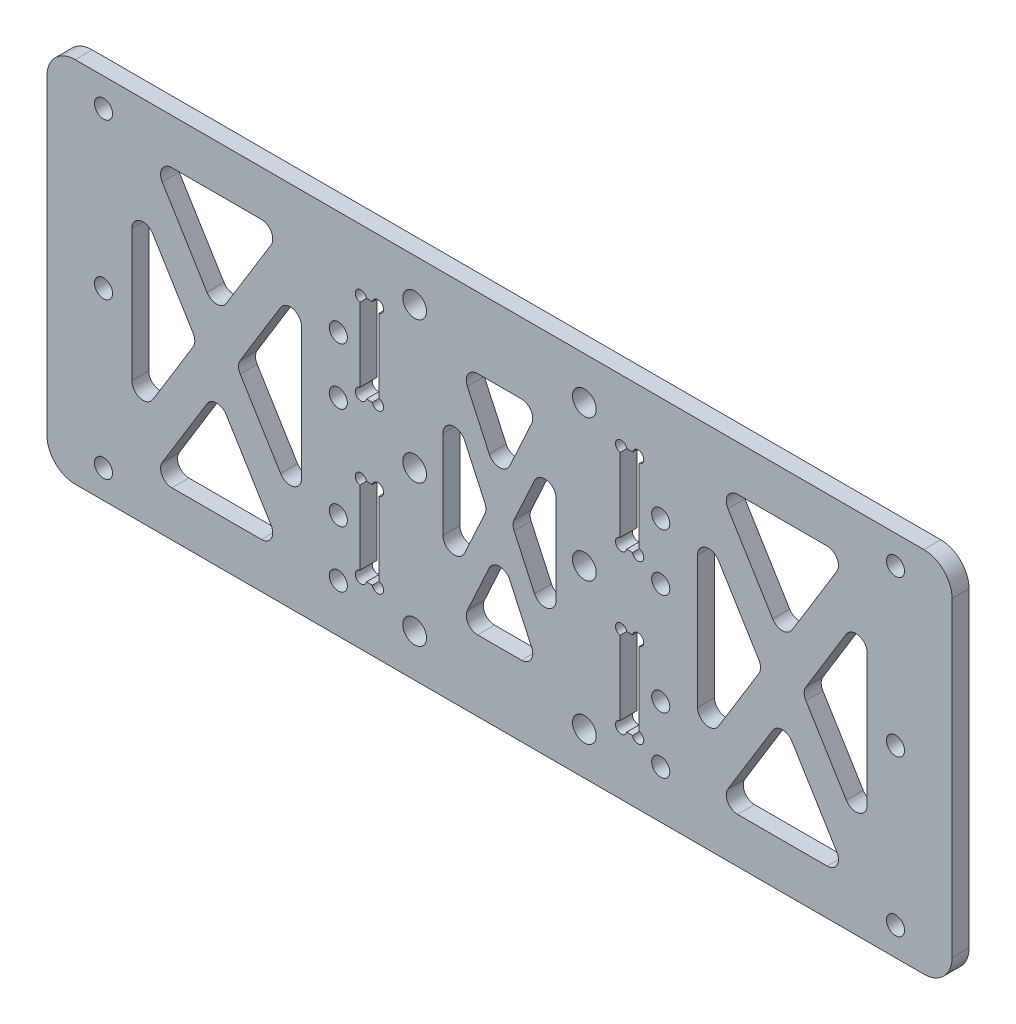
SolidWorks part; units mm, degrees
ref_plane "前视基准面" through (0, 0, 0) normal (0, 0, 1) x (1, 0, 0)
ref_plane "上视基准面" through (0, 0, 0) normal (0, 1, 0) x (1, 0, 0)
ref_plane "右视基准面" through (0, 0, 0) normal (1, 0, 0) x (0, 0, -1)
other "Configuration Table"
sketch "草图1" plane through (0, 0, 0) normal (0, 0, 1) x (1, 0, 0)
  line L1 (0, 0) -> (160, 0)
  line L2 (0, 0) -> (0, 65)
  line L3 (0, 65) -> (160, 65)
  line L4 (160, 0) -> (160, 65)
  dimension "D1" = 160
  dimension "D2" = 65
extrude "凸台-拉伸1" add sketch "草图1" along normal blind 3
sketch "草图2" plane through (0, 0, 3) normal (0, 0, 1) x (1, 0, 0)
  line L0 (80, 65) -> (80, 0) construction
  line L1 (160, 65) -> (0, 65) construction
  line L2 (0, 0) -> (160, 0) construction
  line L3 (150, 0) -> (150, 60) construction
  line L4 (160, 0) -> (160, 65) construction
  circle A0 centre (150, 60) radius 1.6
  circle A1 centre (150, 32.5) radius 1.6
  circle A2 centre (150, 5) radius 1.6
  circle A3 centre (10, 5) radius 1.6
  circle A4 centre (10, 32.5) radius 1.6
  circle A5 centre (10, 60) radius 1.6
  dimension "D2" = 60
  dimension "D3" = 27.5
  dimension "D4" = 27.5
  dimension "D5" = 3.2
  dimension "D1" = 10
extrude "切除-拉伸1" cut sketch "草图2" against normal through all
sketch "草图3" plane through (0, 0, 3) normal (0, 0, 1) x (1, 0, 0)
  line L0 (80, 65) -> (80, 0) construction
  line L1 (160, 65) -> (0, 65) construction
  line L2 (0, 0) -> (160, 0) construction
  line L3 (65, 32.5) -> (80, 32.5) construction
  circle A0 centre (65, 57.5) radius 2.1
  circle A1 centre (65, 32.5) radius 2.1
  circle A3 centre (65, 7.5) radius 2.1
  circle A4 centre (95, 7.5) radius 2.1
  circle A5 centre (95, 32.5) radius 2.1
  circle A6 centre (95, 57.5) radius 2.1
  dimension "D1" = 4.2
  dimension "D2" = 30
  dimension "D3" = 25
extrude "切除-拉伸2" cut sketch "草图3" against normal through all
sketch "草图4" plane through (0, 0, 3) normal (0, 0, 1) x (1, 0, 0)
  line L0 (80, 65) -> (80, 0) construction
  line L1 (160, 65) -> (0, 65) construction
  line L2 (0, 0) -> (160, 0) construction
  line L3 (80, 32.5) -> (70.6836, 32.5) construction
  line L4 (55.5, 54) -> (58.5, 54)
  line L5 (55.5, 54) -> (55.5, 39)
  line L6 (55.5, 39) -> (58.5, 39)
  line L7 (58.5, 54) -> (58.5, 39)
  line L8 (55.5, 26) -> (58.5, 26)
  line L9 (55.5, 11) -> (55.5, 26)
  line L10 (55.5, 11) -> (58.5, 11)
  line L11 (58.5, 11) -> (58.5, 26)
  line L12 (101.5, 11) -> (101.5, 26)
  line L13 (104.5, 11) -> (101.5, 11)
  line L14 (104.5, 11) -> (104.5, 26)
  line L15 (104.5, 26) -> (101.5, 26)
  line L16 (101.5, 54) -> (101.5, 39)
  line L17 (104.5, 39) -> (101.5, 39)
  line L18 (104.5, 54) -> (104.5, 39)
  line L19 (104.5, 54) -> (101.5, 54)
  dimension "D1" = 43
  dimension "D2" = 3
  dimension "D3" = 15
  dimension "D4" = 13
extrude "切除-拉伸3" cut sketch "草图4" against normal through all
sketch "草图5" plane through (0, 0, 3) normal (0, 0, 1) x (1, 0, 0)
  circle A0 centre (58.5, 54) radius 1
  circle A1 centre (55.5, 54) radius 1
  circle A2 centre (58.5, 39) radius 1
  circle A3 centre (55.5, 39) radius 1
  circle A4 centre (58.5, 26) radius 1
  circle A5 centre (55.5, 26) radius 1
  circle A6 centre (58.5, 11) radius 1
  circle A7 centre (55.5, 11) radius 1
  circle A8 centre (104.5, 54) radius 1
  circle A9 centre (101.5, 54) radius 1
  circle A10 centre (104.5, 39) radius 1
  circle A11 centre (101.5, 39) radius 1
  circle A12 centre (104.5, 26) radius 1
  circle A13 centre (101.5, 26) radius 1
  circle A14 centre (104.5, 11) radius 1
  circle A15 centre (101.5, 11) radius 1
  dimension "D1" = 2
extrude "切除-拉伸4" cut sketch "草图5" against normal through all
fillet "圆角1" radius 5 4 edges at (160, 0, 1.5) (160, 65, 1.5) (0, 0, 1.5) (0, 65, 1.5)
sketch "草图6" plane through (0, 0, 3) normal (0, 0, 1) x (1, 0, 0)
  line L0 (108.5, 52.8013) -> (108.5, -0.3338) construction
  line L1 (155, 65) -> (5, 65) construction
  line L2 (80, 65) -> (80, 0) construction
  line L3 (5, 0) -> (155, 0) construction
  line L4 (104.5, 12) -> (104.5, 25) construction
  circle A0 centre (108.5, 46.5) radius 1.6
  circle A1 centre (108.5, 36.5) radius 1.6
  circle A2 centre (108.5, 18.5) radius 1.6
  circle A3 centre (108.5, 8.5) radius 1.6
  circle A4 centre (51.5, 8.5) radius 1.6
  circle A5 centre (51.5, 18.5) radius 1.6
  circle A6 centre (51.5, 36.5) radius 1.6
  circle A7 centre (51.5, 46.5) radius 1.6
  dimension "D1" = 18.5
  dimension "D2" = 10
  dimension "D3" = 18
  dimension "D4" = 10
  dimension "D5" = 3.2
  dimension "D6" = 4
extrude "切除-拉伸5" cut sketch "草图6" against normal blind 10
sketch "草图7" plane through (0, 0, 3) normal (0, 0, 1) x (1, 0, 0)
  line L0 (155, 65) -> (5, 65) construction
  line L1 (115, 57) -> (145, 57)
  line L2 (115, 57) -> (115, 8)
  line L3 (115, 8) -> (145, 8)
  line L4 (145, 57) -> (145, 8)
  line L5 (5, 0) -> (155, 0) construction
  line L6 (160, 5) -> (160, 60) construction
  line L7 (80, 65) -> (80, 0) construction
  line L8 (15, 57) -> (15, 8)
  line L9 (45, 8) -> (15, 8)
  line L10 (45, 57) -> (45, 8)
  line L11 (45, 57) -> (15, 57)
  dimension "D1" = 8
  dimension "D2" = 8
  dimension "D3" = 15
  dimension "D4" = 30
extrude "切除-拉伸6" cut sketch "草图7" against normal blind 10
sketch "草图8" plane through (0, 0, 3) normal (0, 0, 1) x (1, 0, 0)
  line L0 (80, 52.5) -> (80, 65) construction
  line L1 (70, 52.5) -> (90, 52.5)
  line L2 (70, 52.5) -> (70, 12.5)
  line L3 (70, 12.5) -> (90, 12.5)
  line L4 (90, 52.5) -> (90, 12.5)
  line L5 (155, 65) -> (5, 65) construction
  line L6 (90, 32.5) -> (160, 32.5) construction
  line L7 (160, 5) -> (160, 60) construction
  dimension "D1" = 20
  dimension "D2" = 40
extrude "切除-拉伸7" cut sketch "草图8" against normal blind 10
sketch "草图9" plane through (0, 0, 3) normal (0, 0, 1) x (1, 0, 0)
  line L0 (115, 13.7454) -> (115, 8)
  line L2 (90, 15.5496) -> (90, 12.5)
  line L4 (141.4824, 57) -> (130, 38.2454)
  line L5 (115, 51.2546) -> (126.4824, 32.5)
  line L6 (87, 52.5) -> (80, 37.2851)
  line L7 (70, 49.4504) -> (77.7985, 32.5)
  line L8 (145, 51.2546) -> (133.5176, 32.5)
  line L9 (118.5176, 57) -> (130, 38.2454)
  line L10 (90, 49.4504) -> (82.2015, 32.5)
  line L11 (73, 52.5) -> (80, 37.2851)
  line L12 (115, 57) -> (115, 51.2546)
  line L13 (115, 8) -> (118.5176, 8)
  line L14 (145, 57) -> (145, 51.2546)
  line L15 (115, 57) -> (118.5176, 57)
  line L16 (70, 52.5) -> (73, 52.5)
  line L17 (90, 52.5) -> (90, 49.4504)
  line L18 (70, 12.5) -> (73, 12.5)
  line L19 (70, 52.5) -> (70, 49.4504)
  line L20 (87, 12.5) -> (90, 12.5)
  line L21 (87, 52.5) -> (90, 52.5)
  line L22 (70, 12.5) -> (90, 12.5) construction
  line L23 (90, 52.5) -> (70, 52.5) construction
  line L24 (70, 15.5496) -> (70, 12.5)
  line L25 (141.4824, 8) -> (145, 8)
  line L26 (77.7985, 32.5) -> (70, 15.5496)
  line L27 (80, 65) -> (80, 52.5) construction
  line L28 (155, 65) -> (5, 65) construction
  line L29 (80, 27.7149) -> (87, 12.5)
  line L30 (80, 27.7149) -> (73, 12.5)
  line L31 (145, 13.7454) -> (145, 8)
  line L32 (82.2015, 32.5) -> (90, 15.5496)
  line L33 (30, 26.7546) -> (41.4824, 8)
  line L34 (115, 57) -> (118.5176, 57)
  line L35 (141.4824, 57) -> (145, 57)
  line L36 (141.4824, 57) -> (145, 57)
  line L37 (30, 26.7546) -> (18.5176, 8)
  line L38 (126.4824, 32.5) -> (115, 13.7454)
  line L39 (26.4824, 32.5) -> (15, 13.7454)
  line L41 (133.5176, 32.5) -> (145, 13.7454)
  line L42 (130, 26.7546) -> (141.4824, 8)
  line L43 (130, 26.7546) -> (118.5176, 8)
  line L44 (33.5176, 32.5) -> (45, 13.7454)
  line L45 (18.5176, 57) -> (15, 57)
  line L46 (18.5176, 57) -> (15, 57)
  line L47 (45, 57) -> (41.4824, 57)
  line L48 (15, 13.7454) -> (15, 8)
  line L49 (18.5176, 8) -> (15, 8)
  line L50 (45, 57) -> (41.4824, 57)
  line L51 (15, 57) -> (15, 51.2546)
  line L52 (45, 8) -> (41.4824, 8)
  line L53 (45, 57) -> (45, 51.2546)
  line L54 (41.4824, 57) -> (30, 38.2454)
  line L55 (15, 51.2546) -> (26.4824, 32.5)
  line L56 (45, 51.2546) -> (33.5176, 32.5)
  line L57 (18.5176, 57) -> (30, 38.2454)
  line L58 (45, 13.7454) -> (45, 8)
  dimension "D3" = 4
  dimension "D4" = 4
  dimension "D5" = 3
extrude "凸台-拉伸2" add sketch "草图9" against normal through all contours L58 L44 L56 L53 L47 L54 L57 L45 L51 L55 L39 L48 L49 L37 L33 L52 | L32 L10 L17 L21 L6 L11 L16 L19 L7 L26 L24 L18 L30 L29 L20 L2 | L43 L42 L25 L31 L41 L8 L14 L35 L4 L9 L15 L12 L5 L38 L0 L13
fillet "圆角3" radius 2 36 edges at (141.4824, 57, 1.5) (118.5176, 57, 1.5) (130, 38.2454, 1.5) (145, 13.7454, 1.5) (145, 51.2546, 1.5) (133.5176, 32.5, 1.5) (118.5176, 8, 1.5) (141.4824, 8, 1.5) (130, 26.7546, 1.5) (115, 51.2546, 1.5) (115, 13.7454, 1.5) (126.4824, 32.5, 1.5) (15, 51.2546, 1.5) (15, 13.7454, 1.5) (26.4824, 32.5, 1.5) (18.5176, 8, 1.5) (30, 26.7546, 1.5) (41.4824, 8, 1.5) (45, 13.7454, 1.5) (33.5176, 32.5, 1.5) (45, 51.2546, 1.5) (41.4824, 57, 1.5) (30, 38.2454, 1.5) (18.5176, 57, 1.5) (77.7985, 32.5, 1.5) (70, 15.5496, 1.5) (70, 49.4504, 1.5) (73, 12.5, 1.5) (87, 12.5, 1.5) (80, 27.7149, 1.5) (90, 15.5496, 1.5) (90, 49.4504, 1.5) (82.2015, 32.5, 1.5) (87, 52.5, 1.5) (80, 37.2851, 1.5) (73, 52.5, 1.5)
sketch "草图10" plane through (0, 0, 3) normal (0, 0, 1) x (1, 0, 0)
  line L0 (103.5, 54) -> (102.5, 54) construction
  line L1 (101.3, 54.2) -> (104.7, 54.2)
  line L2 (101.3, 54.2) -> (101.3, 38.8)
  line L3 (101.3, 38.8) -> (104.7, 38.8)
  line L4 (104.7, 54.2) -> (104.7, 38.8)
  line L5 (104.5, 40) -> (104.5, 53) construction
  line L6 (101.5, 53) -> (101.5, 40) construction
  line L7 (102.5, 39) -> (103.5, 39) construction
  line L8 (80, 65) -> (80, 52.5) construction
  line L9 (155, 65) -> (5, 65) construction
  line L10 (83.8783, 52.5) -> (76.1217, 52.5) construction
  line L11 (160, 32.5) -> (145, 32.5) construction
  line L12 (160, 5) -> (160, 60) construction
  line L13 (145, 20.8424) -> (145, 44.1576) construction
  line L14 (104.7, 10.8) -> (104.7, 26.2)
  line L15 (101.3, 26.2) -> (104.7, 26.2)
  line L16 (101.3, 10.8) -> (101.3, 26.2)
  line L17 (101.3, 10.8) -> (104.7, 10.8)
  line L18 (58.7, 10.8) -> (55.3, 10.8)
  line L19 (58.7, 10.8) -> (58.7, 26.2)
  line L20 (58.7, 26.2) -> (55.3, 26.2)
  line L21 (55.3, 10.8) -> (55.3, 26.2)
  line L22 (55.3, 54.2) -> (55.3, 38.8)
  line L23 (58.7, 38.8) -> (55.3, 38.8)
  line L24 (58.7, 54.2) -> (58.7, 38.8)
  line L25 (58.7, 54.2) -> (55.3, 54.2)
  dimension "D1" = 0.2
  dimension "D2" = 0.2
  dimension "D3" = 0.2
  dimension "D4" = 0.2
extrude "切除-拉伸8" cut sketch "草图10" against normal through all
